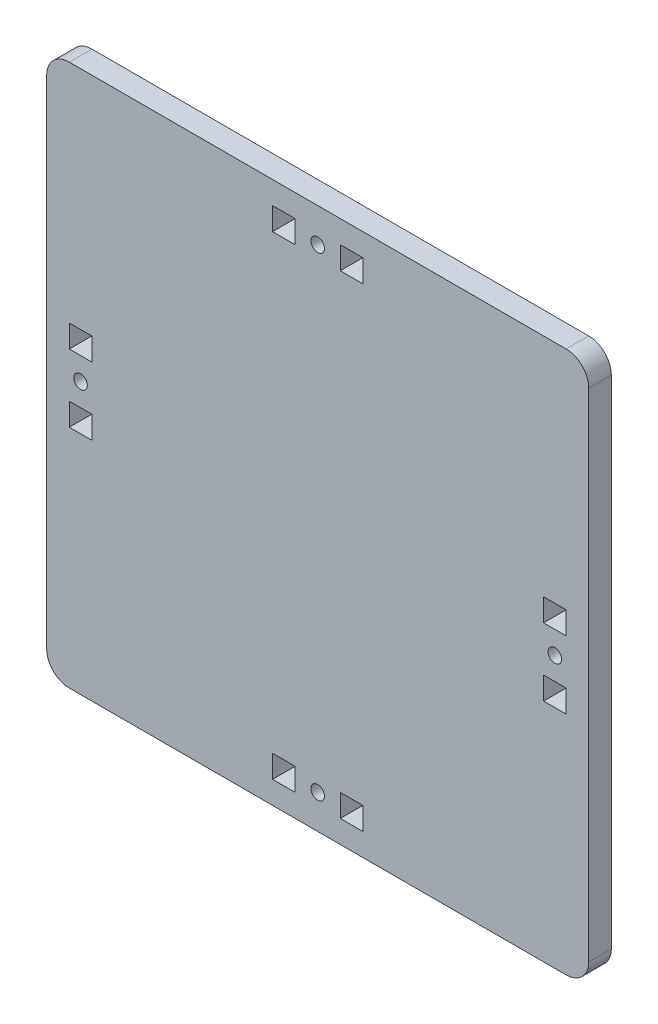
SolidWorks part; units mm, degrees
ref_plane "Front Plane" through (0, 0, 0) normal (0, 0, 1) x (1, 0, 0)
ref_plane "Top Plane" through (0, 0, 0) normal (0, 1, 0) x (1, 0, 0)
ref_plane "Right Plane" through (0, 0, 0) normal (1, 0, 0) x (0, 0, -1)
sketch "Sketch1" plane through (0, 0, 0) normal (0, 0, 1) x (1, 0, 0)
  line L0 (60, 127.4141) -> (60, 63.8722) construction
  line L1 (0, 0) -> (120, 0)
  line L2 (0, 0) -> (0, 120)
  line L3 (0, 120) -> (120, 120)
  line L4 (120, 0) -> (120, 120)
  line L5 (1.2198, 60) -> (112.5, 60) construction
  point P7 (60, 120)
  point P10 (0, 60)
  line B0 (112.5, 55) -> (112.5, 65) construction
  line B1 (110, 55) -> (110, 50)
  line B2 (110, 55) -> (115, 55)
  line B3 (115, 55) -> (115, 50)
  line B4 (110, 50) -> (115, 50)
  line B5 (110, 65) -> (110, 70)
  line B6 (110, 65) -> (115, 65)
  line B7 (115, 65) -> (115, 70)
  line B8 (110, 70) -> (115, 70)
  circle B9 centre (112.5, 60) radius 1.5
  line B10 (7.5, 55) -> (7.5, 65) construction
  line B11 (5, 55) -> (5, 50)
  line B12 (5, 55) -> (10, 55)
  line B13 (10, 55) -> (10, 50)
  line B14 (5, 50) -> (10, 50)
  line B15 (5, 65) -> (5, 70)
  line B16 (5, 65) -> (10, 65)
  line B17 (10, 65) -> (10, 70)
  line B18 (5, 70) -> (10, 70)
  circle B19 centre (7.5, 60) radius 1.5
  line B20 (65, 112.5) -> (55, 112.5) construction
  line B21 (65, 110) -> (70, 110)
  line B22 (65, 110) -> (65, 115)
  line B23 (65, 115) -> (70, 115)
  line B24 (70, 110) -> (70, 115)
  line B25 (55, 110) -> (50, 110)
  line B26 (55, 110) -> (55, 115)
  line B27 (55, 115) -> (50, 115)
  line B28 (50, 110) -> (50, 115)
  line B29 (60, 112.5) -> (60, 106.2198) construction
  circle B30 centre (60, 112.5) radius 1.5
  line B31 (65, 7.5) -> (55, 7.5) construction
  line B32 (65, 10) -> (70, 10)
  line B33 (65, 10) -> (65, 5)
  line B34 (65, 5) -> (70, 5)
  line B35 (70, 10) -> (70, 5)
  line B36 (55, 10) -> (50, 10)
  line B37 (55, 10) -> (55, 5)
  line B38 (55, 5) -> (50, 5)
  line B39 (50, 10) -> (50, 5)
  line B40 (60, 7.5) -> (60, 13.7802) construction
  circle B41 centre (60, 7.5) radius 1.5
  dimension "D2" = 120
  dimension "D3" = 105
  dimension "D5" = 105
sketch_block_instance "Trou M3 plots 5mm-52"
sketch_block "Trou M3 plots 5mm" parameters "D2"=3, "D1"=5, "D3"=5, "D4"=8
sketch_block_instance "Trou M3 plots 5mm-53"
sketch_block_instance "Trou M3 plots 5mm-56"
sketch_block_instance "Trou M3 plots 5mm-58"
extrude "Boss-Extrude1" add sketch "Sketch1" along normal blind 5
fillet "Fillet1" radius 5 4 edges at (0, 0, 2.5) (120, 0, 2.5) (120, 120, 2.5) (0, 120, 2.5)
